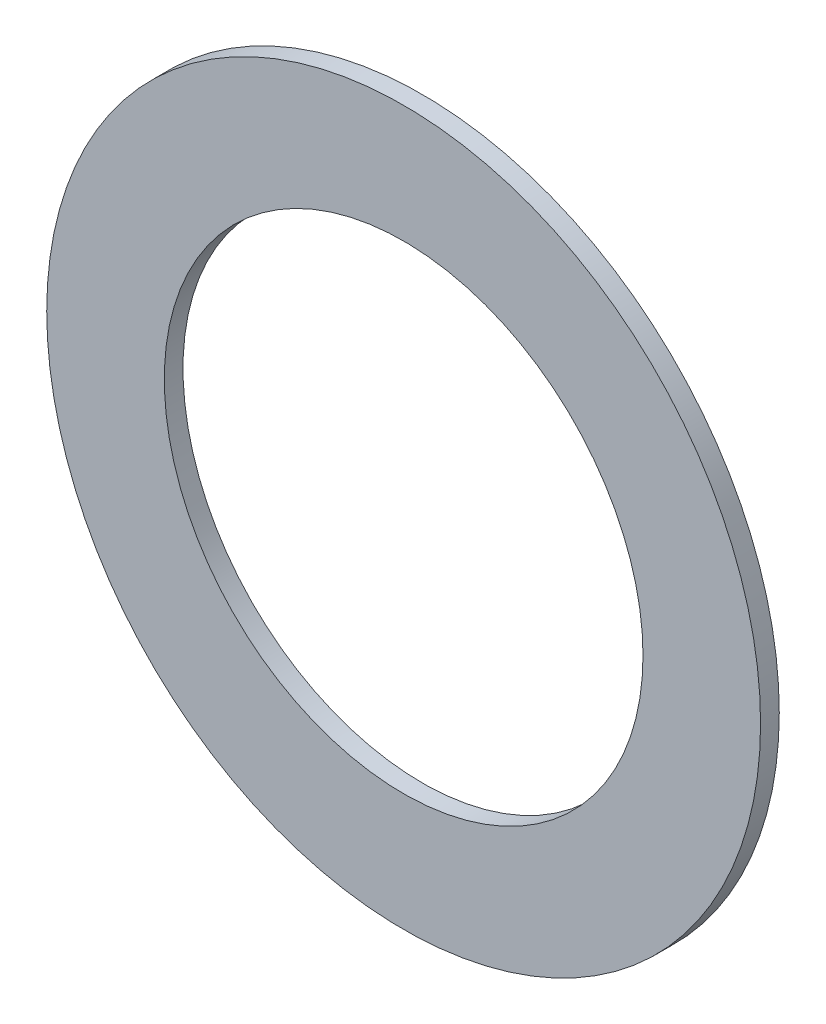
SolidWorks part; units mm, degrees
ref_plane "Front Plane" through (0, 0, 0) normal (0, 0, 1) x (1, 0, 0)
ref_plane "Top Plane" through (0, 0, 0) normal (0, 1, 0) x (1, 0, 0)
ref_plane "Right Plane" through (0, 0, 0) normal (1, 0, 0) x (0, 0, -1)
sketch "Sketch1" plane through (0, 0, 0) normal (0, 0, 1) x (1, 0, 0)
  circle A0 centre (0, 0) radius 76.35
  circle A1 centre (0, 0) radius 51.2
  dimension "D1" = 152.7
  dimension "D2" = 102.4
extrude "Boss-Extrude1" add sketch "Sketch1" along normal blind 4 contours A0 A1
